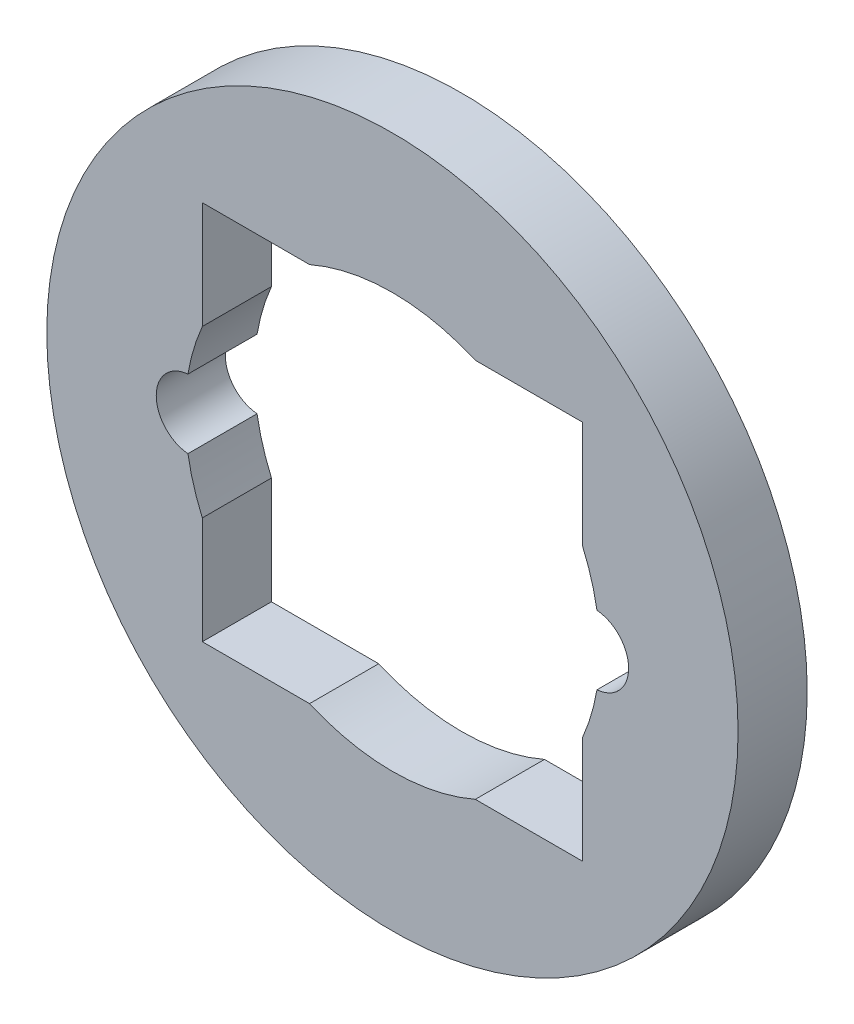
SolidWorks part; units mm, degrees
ref_plane "Front Plane" through (0, 0, 0) normal (0, 0, 1) x (1, 0, 0)
ref_plane "Top Plane" through (0, 0, 0) normal (0, 1, 0) x (1, 0, 0)
ref_plane "Right Plane" through (0, 0, 0) normal (1, 0, 0) x (0, 0, -1)
sketch "Sketch1" plane through (0, 0, 0) normal (0, 0, 1) x (1, 0, 0)
  line L3 (3.5969, 8.25) -> (8.25, 8.25)
  line L58 (-21, -28) -> (21, -28) construction
  line L59 (-21, -25.545) -> (21, -25.545)
  line L60 (-21, -30.455) -> (21, -30.455)
  line L72 (-8.25, 8.25) -> (-3.5969, 8.25)
  line L73 (-8.25, 3.5969) -> (-8.25, 8.25)
  line L74 (-8.25, -8.25) -> (-8.25, -3.5969)
  line L75 (-3.5969, -8.25) -> (-8.25, -8.25)
  line L76 (8.25, -8.25) -> (3.5969, -8.25)
  line L77 (8.25, -3.5969) -> (8.25, -8.25)
  line L78 (8.25, 8.25) -> (8.25, 3.5969)
  circle A0 centre (0, 0) radius 15
  arc A67 (-21, -25.545) -> (-21, -30.455) centre (-21, -28) ccw
  arc A68 (21, -30.455) -> (21, -25.545) centre (21, -28) ccw
  arc A69 (-21, -25.545) -> (-14.8602, -2.043) centre (-46.3433, -6.3712) ccw
  arc A70 (21, -25.545) -> (14.9529, -1.1876) centre (54.4096, -4.3212) cw
  arc A82 (3.5969, 8.25) -> (-3.5969, 8.25) centre (0, 0) ccw
  arc A83 (-8.25, 3.5969) -> (-8.875, 1.4948) centre (0, 0) ccw
  arc A84 (-8.875, 1.4948) -> (-8.875, -1.4948) centre (-8.75, 0) ccw
  arc A85 (-8.875, -1.4948) -> (-8.25, -3.5969) centre (0, 0) ccw
  arc A86 (-3.5969, -8.25) -> (3.5969, -8.25) centre (0, 0) ccw
  arc A87 (8.25, -3.5969) -> (8.875, -1.4948) centre (0, 0) ccw
  arc A88 (8.875, -1.4948) -> (8.875, 1.4948) centre (8.75, 0) ccw
  arc A89 (8.875, 1.4948) -> (8.25, 3.5969) centre (0, 0) ccw
  point P33 (0, -28)
  dimension "D1" = 30
  dimension "D4" = 4.91
  dimension "D5" = 42
extrude "Boss-Extrude1" add sketch "Sketch1" along normal blind 3 contours A0 A89 A88 A87 L77 L76 A86 L75 L74 A85 A84 A83 L73 L72 A82 L3 L78
